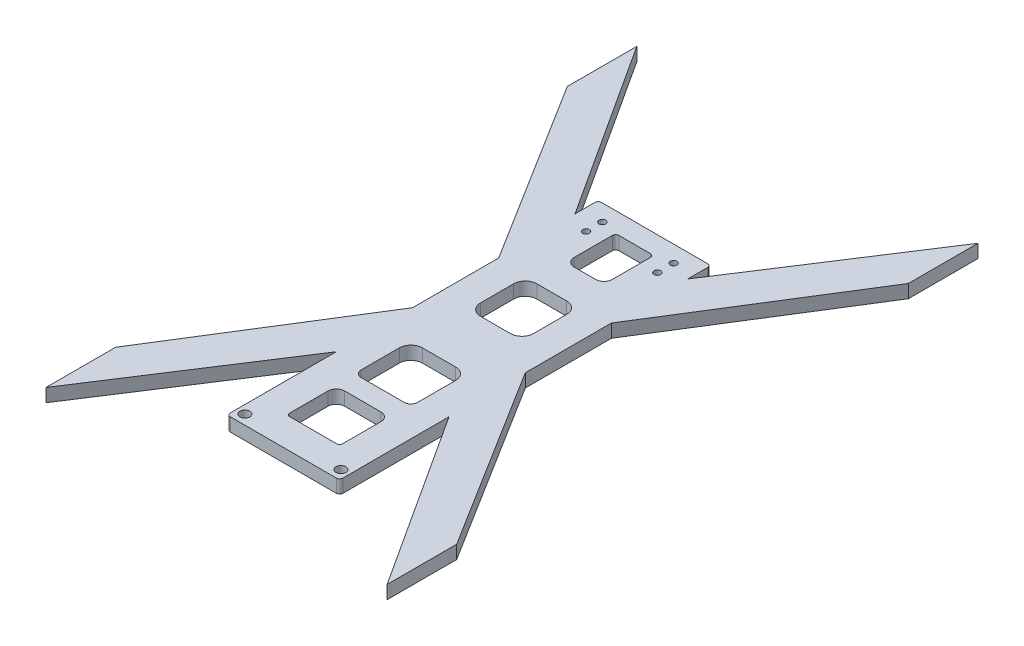
SolidWorks part; units mm, degrees
ref_plane "Front Plane" through (0, 0, 0) normal (0, 0, 1) x (1, 0, 0)
ref_plane "Top Plane" through (0, 0, 0) normal (0, 1, 0) x (1, 0, 0)
ref_plane "Right Plane" through (0, 0, 0) normal (1, 0, 0) x (0, 0, -1)
sketch "Frame Sketch" plane through (0, 0, 0) normal (0, 1, 0) x (1, 0, 0)
  line L0 (2.2808, 0.1404) -> (2.2808, 126.6085) construction
  line L6 (-48.6747, 0) -> (67.0859, 0) construction
  line L11 (2.2808, 0.1404) -> (2.2808, -105.8001) construction
  line L23 (-13.7192, 56.1404) -> (18.2808, 56.1404)
  line L24 (-14.7192, 55.1404) -> (-14.7192, -54.8596)
  line L25 (-13.7192, -55.8596) -> (18.2808, -55.8596)
  line L26 (19.2808, 55.1404) -> (19.2808, -54.8596)
  line L27 (-14.7192, 56.1404) -> (19.2808, -55.8596) construction
  line L28 (-14.7192, -55.8596) -> (19.2808, 56.1404) construction
  line L34 (19.2808, -22.8596) -> (53.7383, -75.9901)
  line L37 (53.7383, -54.9901) -> (53.7383, -75.9901)
  line L38 (19.2808, 0.1404) -> (53.7383, -54.9901)
  line L43 (19.2808, -22.8596) -> (19.2808, 0.1404)
  line L44 (-4.8596, -46.8596) -> (9.4212, -46.8596)
  line L45 (-5.7192, -46) -> (-5.7192, -34.3596)
  line L46 (-3.2192, -31.8596) -> (7.7808, -31.8596)
  line L47 (10.2808, -46) -> (10.2808, -34.3596)
  line L48 (-5.7192, -46.8596) -> (10.2808, -31.8596) construction
  line L49 (-5.7192, -31.8596) -> (10.2808, -46.8596) construction
  line L50 (8.7808, -25.8596) -> (-4.2192, -25.8596)
  line L51 (10.7808, -23.8596) -> (10.7808, -12.3596)
  line L52 (7.2808, -8.8596) -> (-2.7192, -8.8596)
  line L53 (-6.2192, -23.8596) -> (-6.2192, -12.3596)
  line L54 (10.7808, -25.8596) -> (-6.2192, -8.8596) construction
  line L55 (10.7808, -8.8596) -> (-6.2192, -25.8596) construction
  line L56 (-2.2192, 8.1404) -> (6.7808, 8.1404)
  line L57 (-5.7192, 11.6404) -> (-5.7192, 21.6404)
  line L58 (-2.2192, 25.1404) -> (6.7808, 25.1404)
  line L59 (10.2808, 11.6404) -> (10.2808, 21.6404)
  line L60 (-5.7192, 8.1404) -> (10.2808, 25.1404) construction
  line L61 (-5.7192, 25.1404) -> (10.2808, 8.1404) construction
  line L62 (-0.9692, 35.1404) -> (5.5308, 35.1404)
  line L63 (-3.4692, 37.6404) -> (-3.4692, 49.1404)
  line L64 (-2.4692, 50.1404) -> (7.0308, 50.1404)
  line L65 (8.0308, 37.6404) -> (8.0308, 49.1404)
  line L66 (-3.4692, 35.1404) -> (8.0308, 50.1404) construction
  line L67 (-3.4692, 50.1404) -> (8.0308, 35.1404) construction
  line L69 (19.2808, 49.1404) -> (53.7383, 102.2709)
  line L70 (19.2808, 26.1404) -> (53.7383, 81.2709)
  line L71 (53.7383, 81.2709) -> (53.7383, 102.2709)
  line L72 (19.2808, 26.1404) -> (19.2808, 49.1404)
  line L73 (-14.7192, 26.1404) -> (-49.1767, 81.2709)
  line L74 (-49.1767, 81.2709) -> (-49.1767, 102.2709)
  line L75 (-14.7192, 49.1404) -> (-49.1767, 102.2709)
  line L76 (-14.7192, 26.1404) -> (-14.7192, 49.1404)
  line L77 (-14.7192, -22.8596) -> (-49.1767, -75.9901)
  line L78 (-49.1767, -54.9901) -> (-49.1767, -75.9901)
  line L79 (-14.7192, 0.1404) -> (-49.1767, -54.9901)
  line L80 (-14.7192, -22.8596) -> (-14.7192, 0.1404)
  arc A8 (19.2808, 55.1404) -> (18.2808, 56.1404) centre (18.2808, 55.1404) ccw
  arc A9 (19.2808, -54.8596) -> (18.2808, -55.8596) centre (18.2808, -54.8596) cw
  arc A10 (-13.7192, 56.1404) -> (-14.7192, 55.1404) centre (-13.7192, 55.1404) ccw
  arc A11 (-13.7192, -55.8596) -> (-14.7192, -54.8596) centre (-13.7192, -54.8596) cw
  circle A12 centre (-12.2192, -52.9596) radius 1.5
  circle A13 centre (16.7808, -52.9596) radius 1.5
  arc A14 (10.2808, -46) -> (9.4212, -46.8596) centre (9.4212, -46) cw
  arc A15 (-4.8596, -46.8596) -> (-5.7192, -46) centre (-4.8596, -46) cw
  arc A16 (-5.7192, -34.3596) -> (-3.2192, -31.8596) centre (-3.2192, -34.3596) cw
  arc A17 (7.7808, -31.8596) -> (10.2808, -34.3596) centre (7.7808, -34.3596) cw
  arc A18 (10.7808, -23.8596) -> (8.7808, -25.8596) centre (8.7808, -23.8596) cw
  arc A19 (-6.2192, -23.8596) -> (-4.2192, -25.8596) centre (-4.2192, -23.8596) ccw
  arc A20 (10.7808, -12.3596) -> (7.2808, -8.8596) centre (7.2808, -12.3596) ccw
  arc A21 (-2.7192, -8.8596) -> (-6.2192, -12.3596) centre (-2.7192, -12.3596) ccw
  arc A22 (-2.2192, 8.1404) -> (-5.7192, 11.6404) centre (-2.2192, 11.6404) cw
  arc A23 (10.2808, 11.6404) -> (6.7808, 8.1404) centre (6.7808, 11.6404) cw
  arc A24 (-2.2192, 25.1404) -> (-5.7192, 21.6404) centre (-2.2192, 21.6404) ccw
  arc A25 (10.2808, 21.6404) -> (6.7808, 25.1404) centre (6.7808, 21.6404) ccw
  arc A26 (-0.9692, 35.1404) -> (-3.4692, 37.6404) centre (-0.9692, 37.6404) cw
  arc A27 (8.0308, 37.6404) -> (5.5308, 35.1404) centre (5.5308, 37.6404) cw
  arc A28 (-2.4692, 50.1404) -> (-3.4692, 49.1404) centre (-2.4692, 49.1404) ccw
  arc A29 (8.0308, 49.1404) -> (7.0308, 50.1404) centre (7.0308, 49.1404) ccw
  circle A30 centre (13.0308, 51.1404) radius 1
  circle A31 centre (13.0308, 46.2404) radius 1
  circle A32 centre (-8.4692, 51.1404) radius 1
  circle A33 centre (-8.4692, 46.2404) radius 1
  point P0 (0, 0)
  point P6 (0, 0)
  point P18 (56.0705, 67.0918)
  point P19 (50.5864, 87.974)
  point P24 (50.5864, 81.0133)
  point P25 (50.5864, 89.565)
  point P52 (2.2808, -39.3596)
  point P69 (2.2808, -17.3596)
  point P86 (2.2808, 16.6404)
  point P103 (2.2808, 42.6404)
  dimension "D6" = 1
  dimension "D7" = 2.9
  dimension "D8" = 2.5
  dimension "D5" = 17
  dimension "D11" = 9
  dimension "D12" = 9
  dimension "D13" = 10
  dimension "D14" = 33
  dimension "D17" = 23
  dimension "D18" = 21
  dimension "D19" = 26
  dimension "D20" = 7
  dimension "D23" = 23
  dimension "D24" = 21
  dimension "D25" = 1
  dimension "D26" = 1
  dimension "D30" = 5
  dimension "D31" = 5
  dimension "D32" = 4.9
  dimension "D33" = 6
  dimension "D34" = 5
  dimension "D3" = 112
  dimension "D4" = 34
  dimension "D9" = 15
  dimension "D10" = 16
  dimension "D15" = 17
  dimension "D16" = 6
  dimension "D21" = 17
  dimension "D22" = 16
  dimension "D27" = 17
  dimension "D28" = 15
  dimension "D29" = 11.5
extrude "Frame Bottom Plate" add sketch "Frame Sketch" along normal blind 4
